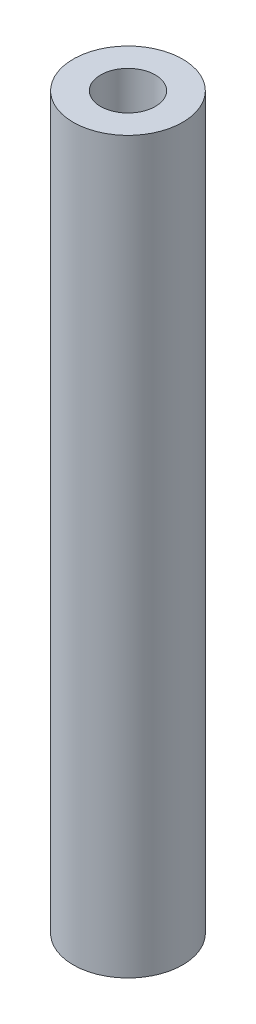
SolidWorks part; units mm, degrees
ref_plane "Front Plane" through (0, 0, 0) normal (0, 0, 1) x (1, 0, 0)
ref_plane "Top Plane" through (0, 0, 0) normal (0, 1, 0) x (1, 0, 0)
ref_plane "Right Plane" through (0, 0, 0) normal (1, 0, 0) x (0, 0, -1)
sketch "Sketch1" plane through (0, 0, 0) normal (0, 1, 0) x (1, 0, 0)
  circle A0 centre (0, 0) radius 3
  point P3 (0, 0)
  dimension "D1" = 6
extrude "Boss-Extrude1" add sketch "Sketch1" along normal blind 40
sketch "Sketch6" plane through (0, 40, 0) normal (0, 1, 0) x (1, 0, 0)
  circle A0 centre (0, 0) radius 1.5
  dimension "D1" = 3
extrude "Cut-Extrude1" cut sketch "Sketch6" against normal through all
